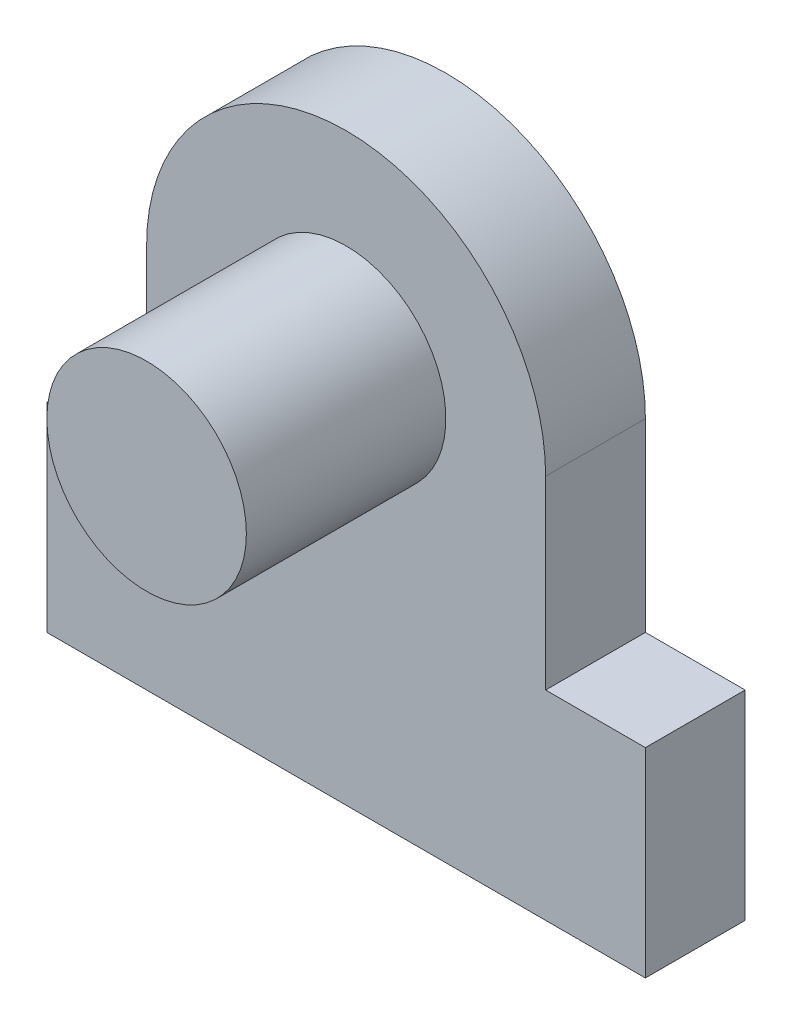
SolidWorks part; units mm, degrees
ref_plane "Front Plane" through (0, 0, 0) normal (0, 0, 1) x (1, 0, 0)
ref_plane "Top Plane" through (0, 0, 0) normal (0, 1, 0) x (1, 0, 0)
ref_plane "Right Plane" through (0, 0, 0) normal (1, 0, 0) x (0, 0, -1)
sketch "Sketch2" plane through (0, 0, 0) normal (0, 0, 1) x (1, 0, 0)
  line L0 (0, 0) -> (10, 0)
  line L1 (10, 0) -> (10, 18.56)
  line L2 (50, 18.56) -> (50, 0)
  line L3 (50, 0) -> (60, 0)
  line L4 (60, 0) -> (60, -20)
  line L5 (60, -20) -> (0, -20)
  line L6 (0, -20) -> (0, 0)
  arc A0 (10, 18.56) -> (50, 18.56) centre (30, 18.56) cw
  dimension "D3" = 20
  dimension "D1" = 20
  dimension "D2" = 60
  dimension "D4" = 38.56
extrude "Boss-Extrude1" add sketch "Sketch2" along normal blind 10
sketch "Sketch3" plane through (0, 0, 10) normal (0, 0, 1) x (1, 0, 0)
  circle A0 centre (30, 18.56) radius 10
  dimension "D1" = 20
extrude "Boss-Extrude2" add sketch "Sketch3" along normal blind 20
